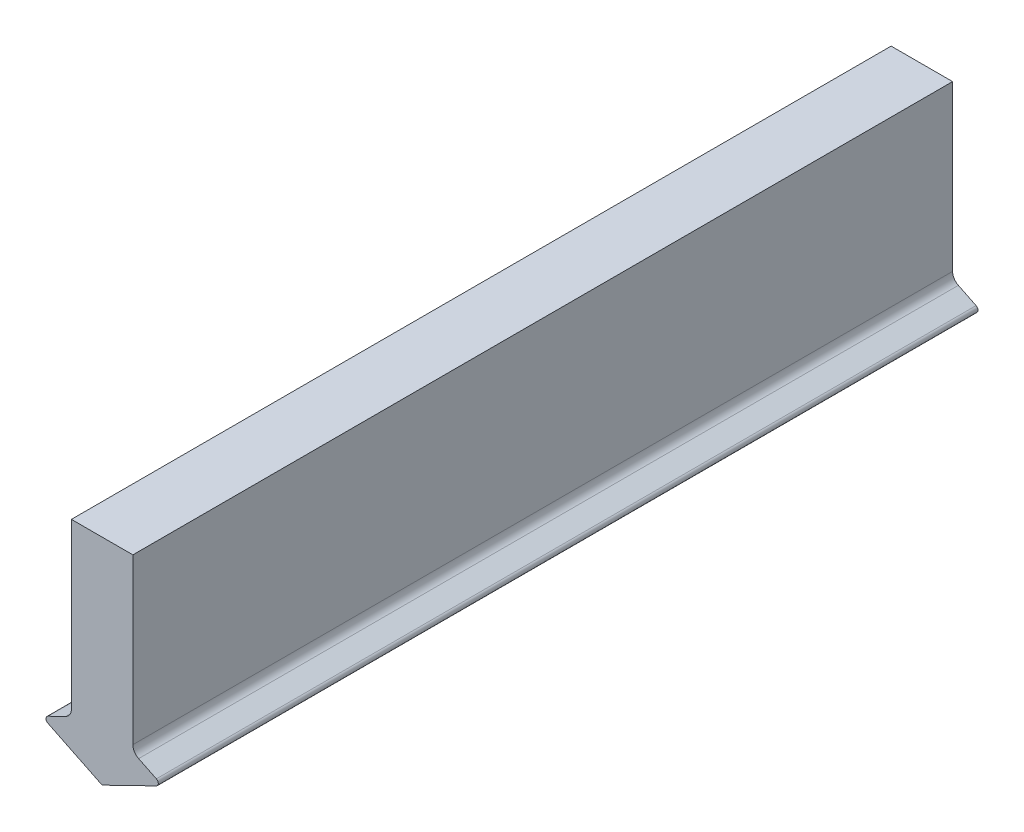
SolidWorks part; units mm, degrees
material "ABS"
ref_plane "Piano frontale" through (0, 0, 0) normal (0, 0, 1) x (1, 0, 0)
ref_plane "Piano superiore" through (0, 0, 0) normal (0, 1, 0) x (1, 0, 0)
ref_plane "Piano destro" through (0, 0, 0) normal (1, 0, 0) x (0, 0, -1)
sketch "Schizzo1" plane through (0, 0, 0) normal (0, 0, 1) x (1, 0, 0)
  line L0 (0, 0) -> (-3.1752, 1.5487)
  line L1 (-3.1752, 1.9082) -> (-2.137, 2.4145)
  line L2 (-1.8, 2.9538) -> (-1.8, 12.5789)
  line L3 (-1.8, 12.5789) -> (1.8, 12.5789)
  line L4 (1.8, 12.5789) -> (1.8, 2.9538)
  line L5 (2.137, 2.4145) -> (3.1752, 1.9082)
  line L6 (3.1752, 1.5487) -> (0, 0)
  line L7 (0, 0) -> (0, 12.5789) construction
  arc A0 (3.1752, 1.5487) -> (3.1752, 1.9082) centre (3.0875, 1.7284) ccw
  arc A1 (-3.1752, 1.9082) -> (-3.1752, 1.5487) centre (-3.0875, 1.7284) ccw
  arc A2 (2.137, 2.4145) -> (1.8, 2.9538) centre (2.4, 2.9538) cw
  arc A3 (-2.137, 2.4145) -> (-1.8, 2.9538) centre (-2.4, 2.9538) ccw
  point P15 (-3.5438, 1.7284)
  point P20 (-1.8, 2.5789)
  dimension "D6" = 0.2
  dimension "D7" = 0.6
  dimension "D1" = 128
  dimension "D2" = 3.9428
  dimension "D3" = 52
  dimension "D4" = 1.9401
  dimension "D5" = 10
extrude "Estrusione-Estrusione1" add sketch "Schizzo1" along normal blind 48
